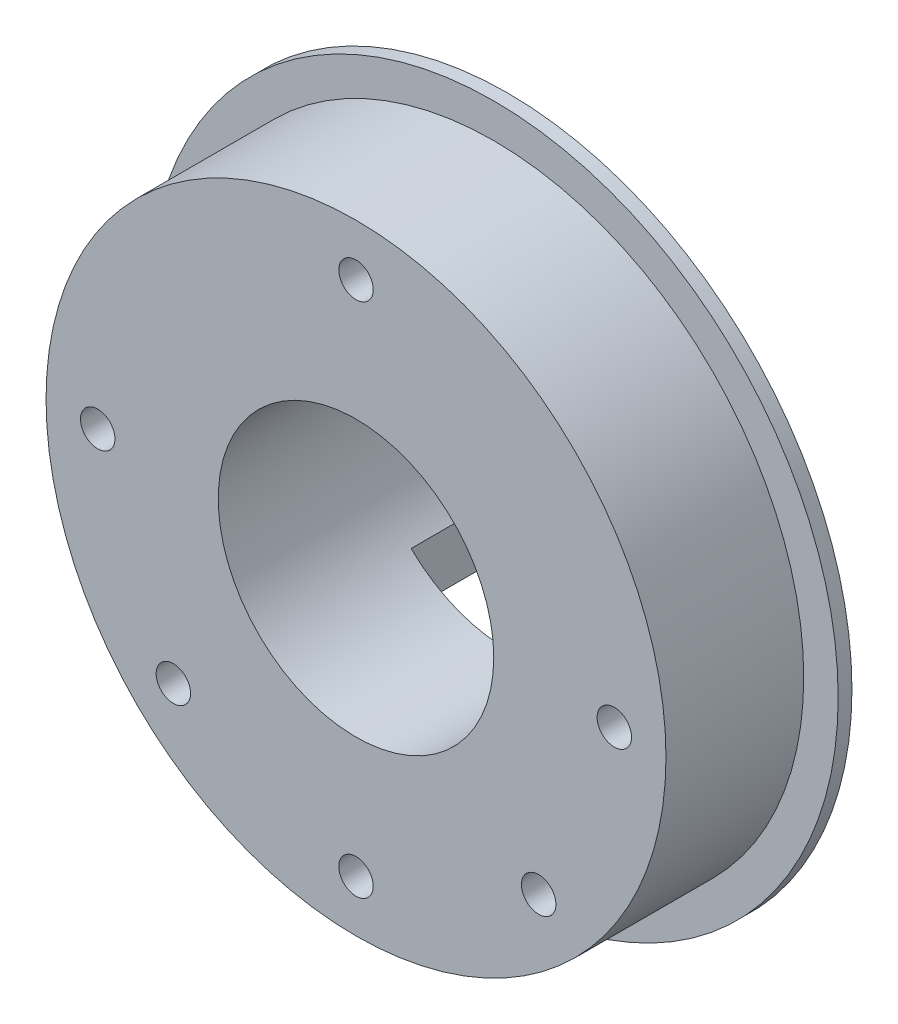
SolidWorks part; units mm, degrees
ref_plane "정면" through (0, 0, 0) normal (0, 0, 1) x (1, 0, 0)
ref_plane "윗면" through (0, 0, 0) normal (0, 1, 0) x (1, 0, 0)
ref_plane "우측면" through (0, 0, 0) normal (1, 0, 0) x (0, 0, -1)
sketch "스케치1" plane through (0, 0, 0) normal (0, 0, 1) x (1, 0, 0)
  circle A0 centre (0, 0) radius 13
  dimension "D1" = 26
extrude "보스-돌출1" add sketch "스케치1" along normal blind 2
sketch "스케치2" plane through (0, 0, 2) normal (0, 0, 1) x (1, 0, 0)
  circle A0 centre (0, 0) radius 13
  circle A1 centre (0, 0) radius 10
  circle A5 centre (0, 0) radius 13 construction
  dimension "D1" = 3
extrude "보스-돌출2" add sketch "스케치2" along normal blind 5
sketch "스케치4" plane through (0, 0, 7) normal (0, 0, 1) x (1, 0, 0)
  circle A0 centre (0, 0) radius 25
  circle A1 centre (0, 0) radius 10
  circle A2 centre (0, 0) radius 10 construction
  dimension "D1" = 50
extrude "보스-돌출3" add sketch "스케치4" along normal blind 1
sketch "스케치5" plane through (0, 0, 8) normal (0, 0, 1) x (1, 0, 0)
  circle A0 centre (0, 0) radius 10
  circle A1 centre (0, 0) radius 22.5
  circle A2 centre (0, 0) radius 10 construction
  dimension "D1" = 45
extrude "보스-돌출4" add sketch "스케치5" along normal blind 10
sketch "스케치6" plane through (0, 0, 18) normal (0, 0, 1) x (1, 0, 0)
  circle A0 centre (0, 0) radius 18.75 construction
  circle A7 centre (0, 18.75) radius 1.25
  circle A9 centre (18.75, 0) radius 1.25
  circle A10 centre (13.2583, -13.2583) radius 1.25
  circle A11 centre (0, -18.75) radius 1.25
  circle A12 centre (-13.2583, -13.2583) radius 1.25
  circle A13 centre (-18.75, 0) radius 1.25
  circle A15 centre (-13.2583, 13.2583) radius 1.25 [skipped]
  circle A16 centre (13.2583, 13.2583) radius 1.25 [skipped]
  point P20 (0, 0)
  point P22 (0, 0)
  dimension "D1" = 37.5
  dimension "D2" = 2.5
  dimension "D3" = 8
extrude "컷-돌출1" cut sketch "스케치6" against normal blind 8
sketch "스케치7" plane through (0, 0, 0) normal (0, 0, -1) x (-1, 0, 0)
  line L0 (7, 3) -> (-7, 3) construction
  line L1 (7, 3) -> (7, -3) construction
  line L2 (-7, 3) -> (-7, -3) construction
  line L3 (7, -3) -> (-7, -3) construction
  line L4 (7, 3) -> (-7, -3) construction
  line L5 (-7, 3) -> (7, -3) construction
  circle A0 centre (0, 0) radius 7 construction
  circle A5 centre (0, 0) radius 3
  circle A6 centre (0, 0) radius 7 construction
  circle A7 centre (0, 0) radius 7 construction
  circle A8 centre (0, 0) radius 7 construction
  circle A9 centre (0, 7) radius 1
  circle A11 centre (0, -7) radius 1
  circle A13 centre (-7, 3) radius 1
  circle A14 centre (-7, -3) radius 1
  circle A15 centre (7, 3) radius 1
  circle A16 centre (7, -3) radius 1
  point P14 (0, -1.0172)
  dimension "D1" = 14
  dimension "D2" = 2
  dimension "D4" = 6
  dimension "D3" = 6
extrude "컷-돌출2" cut sketch "스케치7" against normal through all
sketch "스케치8" plane through (0, 0, 0) normal (0, 1, 0) x (1, 0, 0)
  line L0 (13, 0) -> (-13, 0) construction
  line L1 (-7, -2) -> (7, -2)
  line L2 (-7, -2) -> (-7, -7)
  line L3 (-7, -7) -> (7, -7)
  line L4 (7, -2) -> (7, -7)
  line L5 (-7, -2) -> (7, -7) construction
  line L6 (-7, -7) -> (7, -2) construction
  line L8 (13, -7) -> (13, 0) construction
  line L9 (-13, 0) -> (-13, -7) construction
  line L10 (13, -7) -> (-13, -7) construction
  point P0 (0, -4.5)
  dimension "D1" = 2
  dimension "D3" = 6
  dimension "D4" = 6
extrude "컷-돌출3" cut sketch "스케치8" against normal through all both and the other way through all
